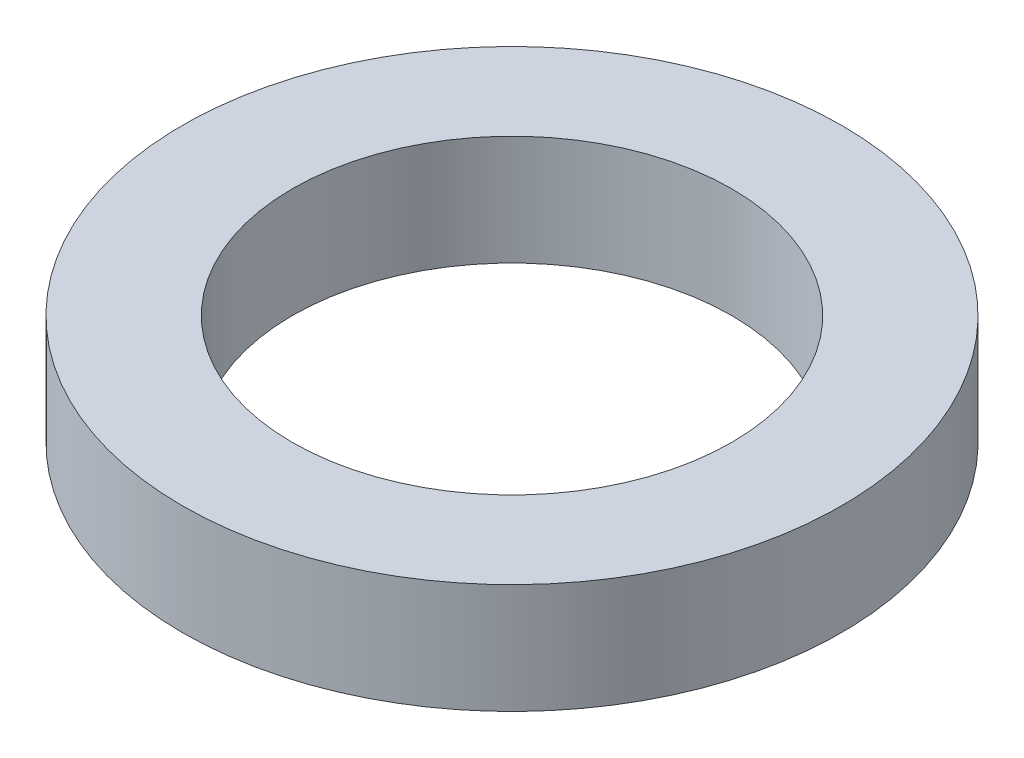
SolidWorks part; units mm, degrees
ref_plane "Front Plane" through (0, 0, 0) normal (0, 0, 1) x (1, 0, 0)
ref_plane "Top Plane" through (0, 0, 0) normal (0, 1, 0) x (1, 0, 0)
ref_plane "Right Plane" through (0, 0, 0) normal (1, 0, 0) x (0, 0, -1)
sketch "Sketch1" plane through (0, 0, 0) normal (0, 1, 0) x (1, 0, 0)
  circle A0 centre (0, 0) radius 15
  circle A1 centre (0, 0) radius 10
  dimension "D1" = 30
  dimension "D2" = 20
extrude "Boss-Extrude1" add sketch "Sketch1" along normal blind 5
